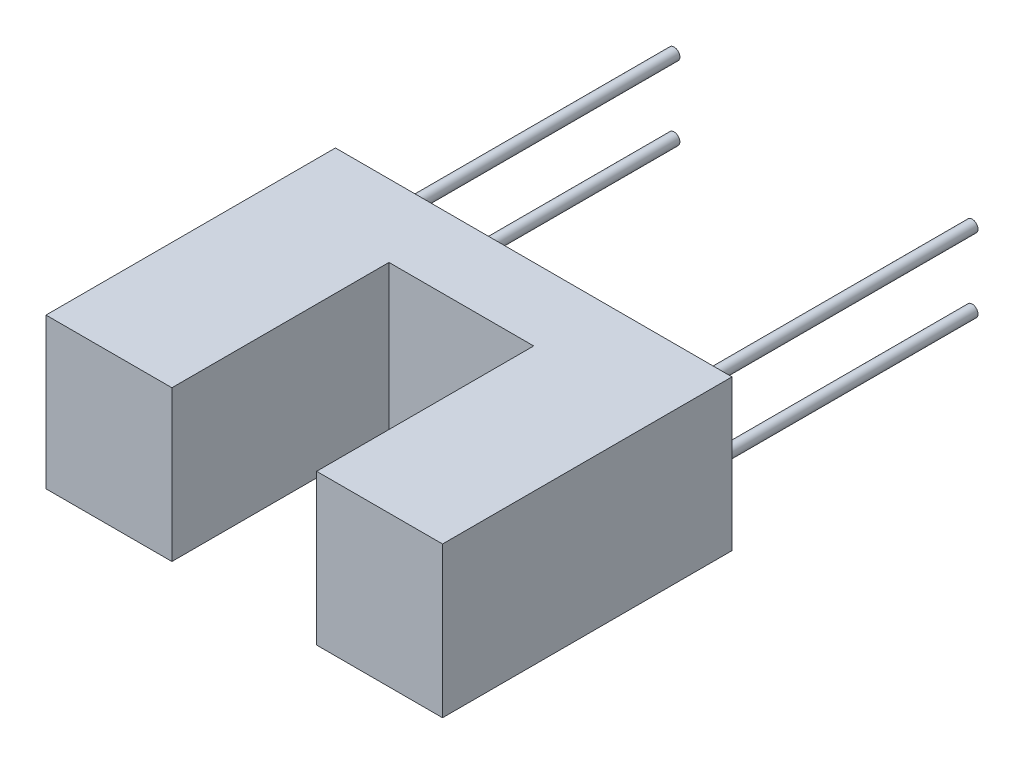
SolidWorks part; units mm, degrees
ref_plane "Front Plane" through (0, 0, 0) normal (0, 0, 1) x (1, 0, 0)
ref_plane "Top Plane" through (0, 0, 0) normal (0, 1, 0) x (1, 0, 0)
ref_plane "Right Plane" through (0, 0, 0) normal (1, 0, 0) x (0, 0, -1)
sketch "Sketch1" plane through (0, 0, 0) normal (0, 1, 0) x (1, 0, 0)
  line L1 (-6.85, -5) -> (6.85, -5)
  line L2 (-6.85, -5) -> (-6.85, 5)
  line L3 (-6.85, 5) -> (6.85, 5)
  line L4 (6.85, -5) -> (6.85, 5)
  line L5 (-6.85, -5) -> (6.85, 5) construction
  line L6 (-6.85, 5) -> (6.85, -5) construction
  point P0 (0, 0)
  dimension "D1" = 10
  dimension "D2" = 13.7
extrude "Boss-Extrude1" add sketch "Sketch1" along normal blind 5.2
sketch "Sketch2" plane through (0, 0, 0) normal (0, -1, 0) x (1, 0, 0)
  line L0 (-6.85, 5) -> (6.85, 5) construction
  line L1 (-2.5, 5) -> (2.5, 5)
  line L2 (-2.5, 5) -> (-2.5, -2.5)
  line L3 (-2.5, -2.5) -> (2.5, -2.5)
  line L4 (2.5, 5) -> (2.5, -2.5)
  line L5 (0, -5) -> (0, 5) construction
  line L6 (6.85, -5) -> (-6.85, -5) construction
  point P11 (0, 5)
  dimension "D1" = 5
  dimension "D2" = 7.5
extrude "Cut-Extrude1" cut sketch "Sketch2" against normal through all
sketch "Sketch3" plane through (0, 0, -5) normal (0, 0, -1) x (-1, 0, 0)
  line L0 (-5.15, 0) -> (-5.15, 5.2) construction
  line L1 (-6.85, 0) -> (6.85, 0) construction
  line L2 (-6.85, 5.2) -> (6.85, 5.2) construction
  line L3 (5.15, 0) -> (5.15, 5.2) construction
  line L4 (5.15, 3.87) -> (5.15, 1.33) construction
  line L5 (-5.15, 2.6) -> (5.15, 2.6) construction
  line L6 (0, 0) -> (0, 5.2) construction
  line L7 (-5.15, 1.33) -> (-5.15, 3.87) construction
  circle A0 centre (-5.15, 3.87) radius 0.2
  circle A1 centre (-5.15, 1.33) radius 0.2
  circle A2 centre (5.15, 3.87) radius 0.2
  circle A3 centre (5.15, 1.33) radius 0.2
  point P13 (0, 2.6)
  point P22 (-5.15, 2.6)
  point P23 (5.15, 2.6)
  dimension "D2" = 0.4
  dimension "D1" = 10.3
  dimension "D3" = 2.54
extrude "Boss-Extrude2" add sketch "Sketch3" along normal blind 10
sketch "Sketch4" plane through (2.5, 0, 0) normal (-1, 0, 0) x (0, 0, 1)
  line L0 (-2.5, 2.6) -> (5, 2.6) construction
  line L1 (-2.5, 5.2) -> (-2.5, 0) construction
  line L2 (5, 5.2) -> (5, 0) construction
  line L3 (2.5, 0) -> (2.5, 5.2) construction
  line L4 (-2.5, 0) -> (5, 0) construction
  line L5 (-2.5, 5.2) -> (5, 5.2) construction
  circle A0 centre (2.5, 2.6) radius 0.3185
  point P14 (0, 0)
  dimension "D1" = 2.5
